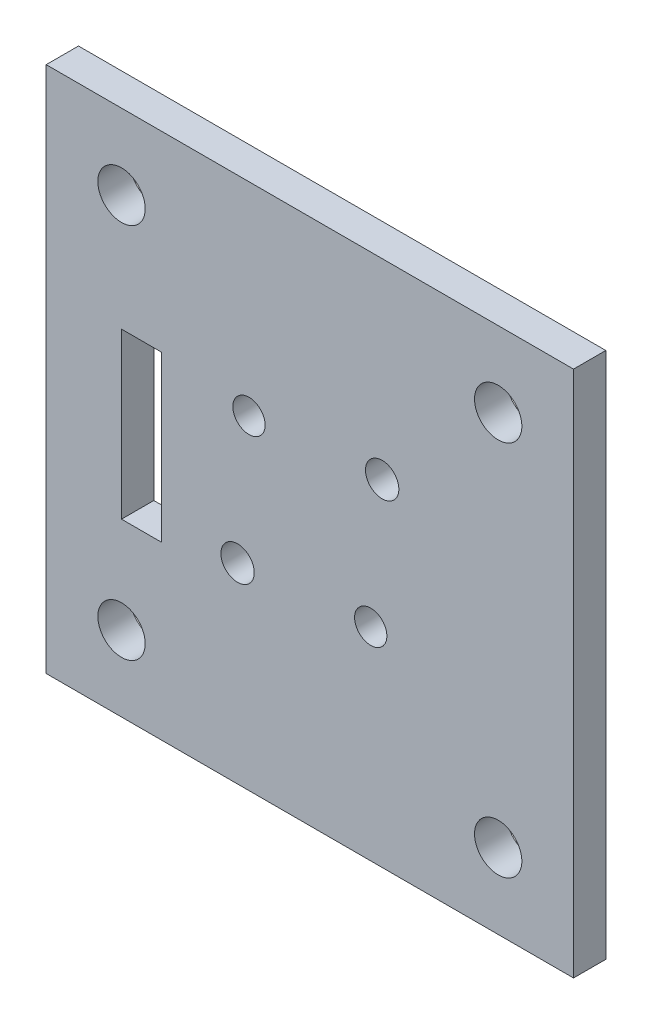
SolidWorks part; units mm, degrees
ref_plane "Front Plane" through (0, 0, 0) normal (0, 0, 1) x (1, 0, 0)
ref_plane "Top Plane" through (0, 0, 0) normal (0, 1, 0) x (1, 0, 0)
ref_plane "Right Plane" through (0, 0, 0) normal (1, 0, 0) x (0, 0, -1)
sketch "Sketch1" plane through (0, 0, 0) normal (0, 0, 1) x (1, 0, 0)
  line L0 (-17.5, 17.5) -> (17.5, 17.5) construction
  line L5 (-24.5, -24.5) -> (24.5, -24.5)
  line L6 (-24.5, -24.5) -> (-24.5, 24.5)
  line L11 (-24.5, 24.5) -> (24.5, 24.5)
  line L13 (24.5, -24.5) -> (24.5, 24.5)
  line L14 (-24.5, -24.5) -> (24.5, 24.5) construction
  line L15 (-24.5, 24.5) -> (24.5, -24.5) construction
  line L20 (-17.5, 17.5) -> (17.5, -17.5) construction
  line L22 (17.5, 17.5) -> (17.5, -17.5) construction
  line L23 (17.5, -17.5) -> (-17.5, -17.5) construction
  line L24 (-17.5, -17.5) -> (-17.5, 17.5) construction
  circle A8 centre (-17.5, 17.5) radius 2.2
  circle A9 centre (17.5, -17.5) radius 2.2
  circle A10 centre (17.5, 17.5) radius 2.2
  circle A11 centre (-17.5, -17.5) radius 2.2
  point P0 (0, 0)
  point P16 (-0.5896, 0.5896)
  dimension "D3" = 4.4
  dimension "D4" = 4.4
  dimension "D5" = 4.4
  dimension "D6" = 4.4
  dimension "D7" = 35
  dimension "D1" = 49
  dimension "D2" = 49
extrude "Boss-Extrude1" add sketch "Sketch1" along normal blind 3 contours L5 L13 L11 L6 A11 A10 A9 A8
sketch "Sketch2" plane through (0, 0, 0) normal (0, 0, -1) x (-1, 0, 0)
  line L0 (-17.5, 17.5) -> (17.5, -17.5) construction
  line L1 (17.5, 17.5) -> (-17.5, -17.5) construction
  line L3 (13.8005, 6.7175) -> (17.5, 6.7175)
  line L4 (13.8005, 6.7175) -> (13.8005, -8.5767)
  line L5 (13.8005, -8.5767) -> (17.5, -8.5767)
  line L6 (17.5, 6.7175) -> (17.5, -8.5767)
  line L7 (13.8005, 6.7175) -> (17.5, -8.5767) construction
  line L8 (13.8005, -8.5767) -> (17.5, 6.7175) construction
  circle A0 centre (-6.7175, 6.7175) radius 1.55
  circle A1 centre (5.6569, 5.6569) radius 1.5
  circle A2 centre (6.7175, -6.7175) radius 1.55
  circle A3 centre (-5.6569, -5.6569) radius 1.5
  point P23 (15.6503, -0.9296)
  dimension "D1" = 3.1
  dimension "D2" = 3.1
  dimension "D3" = 3
  dimension "D4" = 3
  dimension "D5" = 16
  dimension "D6" = 19
extrude "Cut-Extrude1" cut sketch "Sketch2" against normal blind 3
